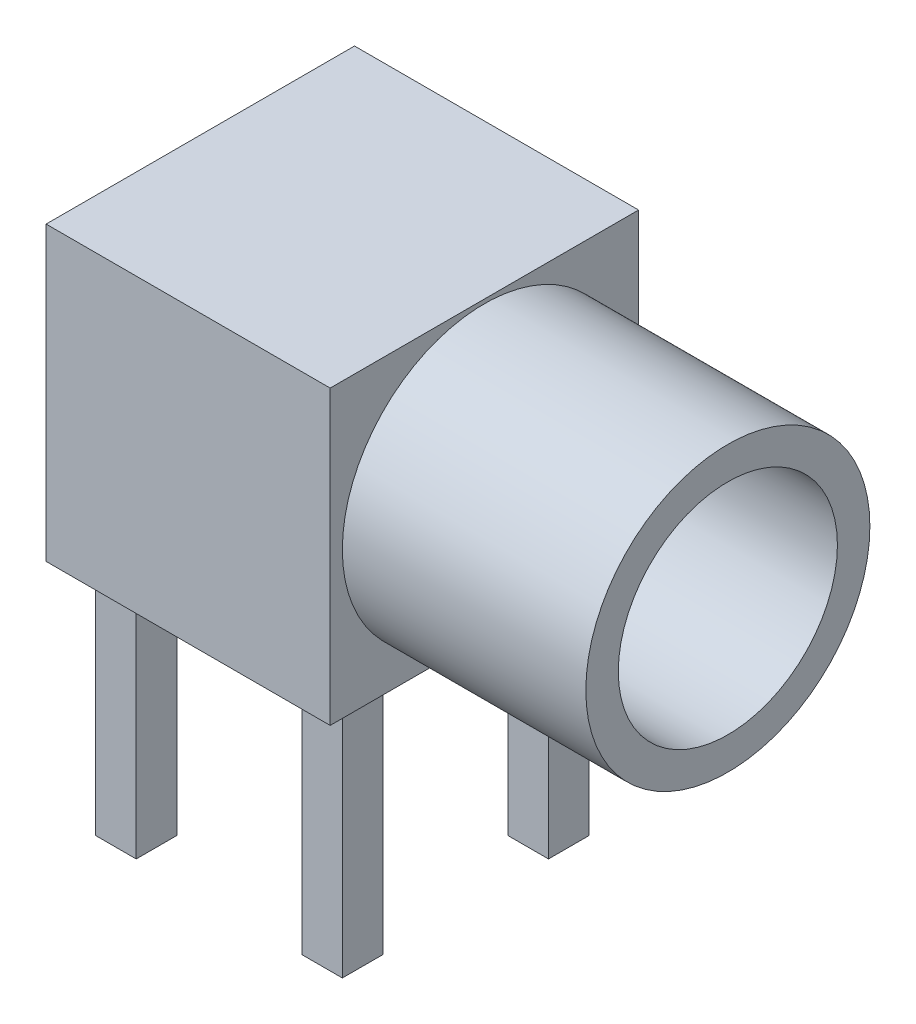
SolidWorks part; units mm, degrees
ref_plane "Front Plane" through (0, 0, 0) normal (0, 0, 1) x (1, 0, 0)
ref_plane "Top Plane" through (0, 0, 0) normal (0, 1, 0) x (1, 0, 0)
ref_plane "Right Plane" through (0, 0, 0) normal (1, 0, 0) x (0, 0, -1)
sketch "Sketch1" plane through (0, 0, 0) normal (0, 1, 0) x (1, 0, 0)
  line L1 (-1.75, 1.9) -> (1.75, 1.9)
  line L2 (-1.75, 1.9) -> (-1.75, -1.9)
  line L3 (-1.75, -1.9) -> (1.75, -1.9)
  line L4 (1.75, 1.9) -> (1.75, -1.9)
  line L5 (-1.75, 1.9) -> (1.75, -1.9) construction
  line L6 (-1.75, -1.9) -> (1.75, 1.9) construction
  point P0 (0, 0)
  dimension "D1" = 3.5
  dimension "D2" = 3.8
extrude "Boss-Extrude1" add sketch "Sketch1" along normal blind 3.6
sketch "Sketch2" plane through (1.75, 0, 0) normal (1, 0, 0) x (0, 0, -1)
  line L2 (-1.9, 0) -> (1.9, 0) construction
  circle A0 centre (0, 1.8) radius 1.75
  circle A1 centre (0, 1.8) radius 1.35
  dimension "D1" = 3.5
  dimension "D3" = 2.7
  dimension "D2" = 1.8
extrude "Boss-Extrude2" add sketch "Sketch2" along normal blind 3
sketch "Sketch3" plane through (0, 0, 0) normal (0, -1, 0) x (1, 0, 0)
  line L0 (-1.02, 1.02) -> (1.02, -1.02) construction
  line L5 (-1.52, 1.52) -> (-1.02, 1.52)
  line L6 (-1.52, 1.52) -> (-1.52, 1.02)
  line L7 (-1.52, 1.02) -> (-1.02, 1.02)
  line L8 (-1.02, 1.52) -> (-1.02, 1.02)
  line L9 (-1.52, -1.02) -> (-1.02, -1.02)
  line L10 (-1.52, -1.02) -> (-1.52, -1.52)
  line L11 (-1.52, -1.52) -> (-1.02, -1.52)
  line L12 (-1.02, -1.02) -> (-1.02, -1.52)
  line L13 (1.02, 1.52) -> (1.52, 1.52)
  line L14 (1.02, 1.52) -> (1.02, 1.02)
  line L15 (1.02, 1.02) -> (1.52, 1.02)
  line L16 (1.52, 1.52) -> (1.52, 1.02)
  line L17 (1.02, -1.02) -> (1.52, -1.02)
  line L18 (1.02, -1.02) -> (1.02, -1.52)
  line L19 (1.02, -1.52) -> (1.52, -1.52)
  line L20 (1.52, -1.02) -> (1.52, -1.52)
  dimension "D1" = 0.5
  dimension "D2" = 2.54
  dimension "D3" = 2.54
extrude "Boss-Extrude3" add sketch "Sketch3" along normal blind 3
